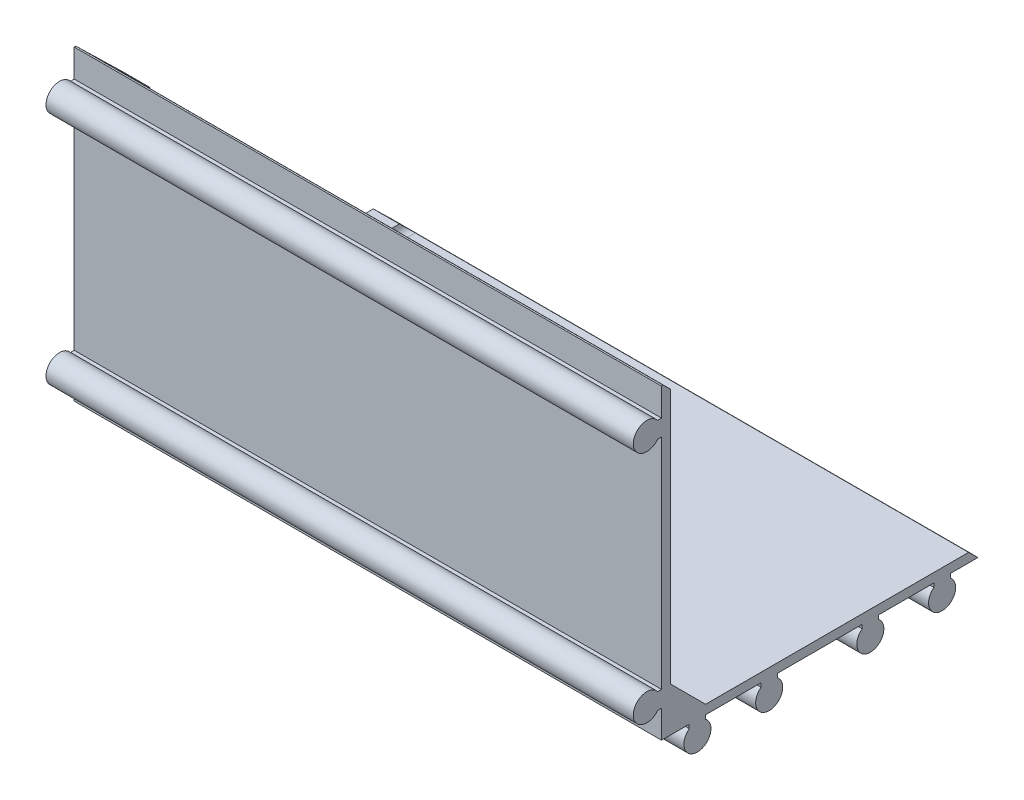
SolidWorks part; units mm, degrees
ref_plane "Спереди" through (0, 0, 0) normal (0, 0, 1) x (1, 0, 0)
ref_plane "Сверху" through (0, 0, 0) normal (0, 1, 0) x (1, 0, 0)
ref_plane "Справа" through (0, 0, 0) normal (1, 0, 0) x (0, 0, -1)
ref_plane "Плоскость4" through (90, 0, 0) normal (1, 0, 0) x (0, 0, -1)
sketch "Эскиз1" plane through (90, 0, 0) normal (1, 0, 0) x (0, 0, -1)
  line L0 (6.75, 160.9062) -> (6.75, 204.25)
  line L1 (6.75, 204.25) -> (-38.0938, 204.25)
  line L2 (-38.0938, 201.75) -> (-37.5, 201.75)
  line L3 (-37.5, 201.75) -> (-37.5, 168.25)
  line L4 (-37.5, 168.25) -> (-38.0938, 168.25)
  line L5 (-38.0938, 165.75) -> (-37.5, 165.75)
  line L6 (-37.5, 165.75) -> (-37.5, 161.5)
  line L7 (-37.5, 161.5) -> (-33.25, 161.5)
  line L8 (-33.25, 161.5) -> (-33.25, 160.9062)
  line L9 (-30.75, 160.9062) -> (-30.75, 161.5)
  line L10 (-30.75, 161.5) -> (-22.25, 161.5)
  line L11 (-22.25, 161.5) -> (-22.25, 160.9062)
  line L12 (-19.75, 160.9062) -> (-19.75, 161.5)
  line L13 (-19.75, 161.5) -> (-6.75, 161.5)
  line L14 (-6.75, 161.5) -> (-6.75, 160.9062)
  line L15 (-4.25, 160.9062) -> (-4.25, 161.5)
  line L16 (-4.25, 161.5) -> (4.25, 161.5)
  line L17 (4.25, 161.5) -> (4.25, 160.9062)
  arc A0 (-38.0938, 204.25) -> (-38.0938, 201.75) centre (-39.75, 203) ccw
  arc A1 (-38.0938, 168.25) -> (-38.0938, 165.75) centre (-39.75, 167) ccw
  arc A2 (-33.25, 160.9062) -> (-30.75, 160.9062) centre (-32, 159.25) ccw
  arc A3 (-22.25, 160.9062) -> (-19.75, 160.9062) centre (-21, 159.25) ccw
  arc A4 (-6.75, 160.9062) -> (-4.25, 160.9062) centre (-5.5, 159.25) ccw
  arc A5 (4.25, 160.9062) -> (6.75, 160.9062) centre (5.5, 159.25) ccw
extrude "Бобышка-Вытянуть1" add sketch "Эскиз1" against normal blind 90
sketch "Эскиз2" plane through (0, 0, -6.75) normal (0, 0, -1) x (-1, 0, 0)
  line L0 (0, 204.25) -> (0, 161.5)
  line L1 (0, 161.5) -> (-90, 161.5)
  line L2 (-90, 161.5) -> (-90, 204.25)
  line L3 (-90, 204.25) -> (0, 204.25)
extrude "Бобышка-Вытянуть2" add sketch "Эскиз2" along normal blind 8.2
sketch "Эскиз3" plane through (0, 204.25, 0) normal (0, 1, 0) x (-1, 0, 0)
  line L0 (-90, -14.95) -> (-90, 37.5)
  line L1 (-90, 37.5) -> (0, 37.5)
  line L2 (0, 37.5) -> (0, -14.95)
  line L3 (0, -14.95) -> (-90, -14.95)
extrude "Бобышка-Вытянуть3" add sketch "Эскиз3" along normal blind 8.2
sketch "Эскиз4" plane through (0, 0, 0) normal (-1, 0, 0) x (0, 0, 1)
  line L0 (-14.95, 161.5) -> (-11, 161.5)
  line L1 (-11, 161.5) -> (-11, 163.75)
  line L2 (-11, 163.75) -> (-14.95, 163.75)
  line L3 (-14.95, 163.75) -> (-14.95, 161.5)
extrude "Вырез-Вытянуть1" cut sketch "Эскиз4" against normal through all
sketch "Эскиз5" plane through (0, 0, 0) normal (-1, 0, 0) x (0, 0, 1)
  line L0 (-14.95, 170.25) -> (-11, 170.25)
  line L1 (-11, 170.25) -> (-11, 199.75)
  line L2 (-11, 199.75) -> (-14.95, 199.75)
  line L3 (-14.95, 199.75) -> (-14.95, 170.25)
extrude "Вырез-Вытянуть2" cut sketch "Эскиз5" against normal through all
sketch "Эскиз6" plane through (0, 0, 0) normal (-1, 0, 0) x (0, 0, 1)
  line L0 (-14.95, 212.45) -> (-14.95, 206.25)
  line L1 (-14.95, 206.25) -> (-11, 206.25)
  line L2 (-11, 206.25) -> (-11, 212.45)
  line L3 (-11, 212.45) -> (-14.95, 212.45)
extrude "Вырез-Вытянуть3" cut sketch "Эскиз6" against normal through all
sketch "Эскиз7" plane through (0, 0, 0) normal (-1, 0, 0) x (0, 0, 1)
  line L0 (-11, 212.45) -> (-11, 208.5)
  line L1 (-11, 208.5) -> (-8.75, 208.5)
  line L2 (-8.75, 208.5) -> (-8.75, 212.45)
  line L3 (-8.75, 212.45) -> (-11, 212.45)
extrude "Вырез-Вытянуть4" cut sketch "Эскиз7" against normal through all
sketch "Эскиз8" plane through (0, 0, 0) normal (-1, 0, 0) x (0, 0, 1)
  line L0 (-2.25, 212.45) -> (-2.25, 208.5)
  line L1 (-2.25, 208.5) -> (2.25, 208.5)
  line L2 (2.25, 208.5) -> (2.25, 212.45)
  line L3 (2.25, 212.45) -> (-2.25, 212.45)
extrude "Вырез-Вытянуть5" cut sketch "Эскиз8" against normal through all
sketch "Эскиз9" plane through (0, 0, 0) normal (-1, 0, 0) x (0, 0, 1)
  line L0 (8.75, 212.45) -> (8.75, 208.5)
  line L1 (8.75, 208.5) -> (17.75, 208.5)
  line L2 (17.75, 208.5) -> (17.75, 212.45)
  line L3 (17.75, 212.45) -> (8.75, 212.45)
extrude "Вырез-Вытянуть6" cut sketch "Эскиз9" against normal through all
sketch "Эскиз10" plane through (0, 0, 0) normal (-1, 0, 0) x (0, 0, 1)
  line L0 (24.25, 212.45) -> (24.25, 208.5)
  line L1 (24.25, 208.5) -> (28.75, 208.5)
  line L2 (28.75, 208.5) -> (28.75, 212.45)
  line L3 (28.75, 212.45) -> (24.25, 212.45)
extrude "Вырез-Вытянуть7" cut sketch "Эскиз10" against normal through all
sketch "Эскиз11" plane through (0, 0, 0) normal (-1, 0, 0) x (0, 0, 1)
  line L0 (37.5, 212.45) -> (35.25, 212.45)
  line L1 (35.25, 212.45) -> (35.25, 208.5)
  line L2 (35.25, 208.5) -> (37.5, 208.5)
  line L3 (37.5, 208.5) -> (37.5, 212.45)
extrude "Вырез-Вытянуть8" cut sketch "Эскиз11" against normal through all
sketch "Эскиз12" plane through (90, 0, 0) normal (1, 0, 0) x (0, 0, -1)
  line L0 (9.6, 207.1) -> (-36.1, 207.1)
  line L1 (-36.1, 207.1) -> (-36.1, 162.9)
  line L2 (-36.1, 162.9) -> (9.6, 162.9)
  line L3 (9.6, 162.9) -> (9.6, 207.1)
extrude "Вырез-Вытянуть9" cut sketch "Эскиз12" against normal blind 86
hole_wizard "Диаметр отверстия Ø2.5 (2.5)1" positions "Эскиз14" profile "Эскиз13" hole size "Ø2.5" standard "Ansi Metric"
sketch "Эскиз14" plane through (90, 0, 0) normal (1, 0, 0) x (0, 0, -1)
  point P0 (5.5, 159.25)
  point P1 (-21, 159.25)
  point P2 (-5.5, 159.25)
  point P3 (-32, 159.25)
  point P4 (-39.75, 167)
  point P5 (-39.75, 203)
sketch "Эскиз13" plane through (90, 159.25, -5.5) normal (0, 1, 0) x (0, 0, -1)
  line L0 (0, 0) -> (0, 90)
  line L1 (0, 90) -> (1.25, 90)
  line L2 (1.25, 90) -> (1.25, 0)
  line L5 (1.25, 0) -> (0, 0)
  line L11 (0, -6.35) -> (0, 107.95) construction
  dimension "Диаметр сквозного отверстия" = 2.5
  dimension "Глубина сквозного отверстия" = 90
hole_wizard "Диаметр отверстия Ø4.5 (4.5)1" positions "Эскиз16" profile "Эскиз15" hole size "Ø4.5" standard "Ansi Metric"
sketch "Эскиз16" plane through (0, 0, 0) normal (-1, 0, 0) x (0, 0, 1)
  point P0 (-13.25, 167)
  point P1 (-13.25, 203)
  point P2 (-5.5, 210.75)
  point P3 (5.5, 210.75)
  point P4 (21, 210.75)
  point P5 (32, 210.75)
sketch "Эскиз15" plane through (0, 167, -13.25) normal (0, 1, 0) x (0, 0, 1)
  line L0 (0, 0) -> (0, 90)
  line L1 (0, 90) -> (2.25, 90)
  line L2 (2.25, 90) -> (2.25, 0)
  line L5 (2.25, 0) -> (0, 0)
  line L11 (0, -6.35) -> (0, 107.95) construction
  dimension "Диаметр сквозного отверстия" = 4.5
  dimension "Глубина сквозного отверстия" = 90
hole_wizard "Диаметр отверстия Ø8.3 (8.3)1" positions "Эскиз18" profile "Эскиз17" hole size "Ø8.3" standard "Ansi Metric"
sketch "Эскиз18" plane through (0, 0, 0) normal (-1, 0, 0) x (0, 0, 1)
  point P0 (13.25, 185)
sketch "Эскиз17" plane through (0, 185, 13.25) normal (0, 1, 0) x (0, 0, 1)
  line L0 (0, 0) -> (0, 3.2)
  line L1 (0, 3.2) -> (4.15, 3.2)
  line L2 (4.15, 3.2) -> (4.15, 0)
  line L5 (4.15, 0) -> (0, 0)
  line L10 (0, 3.2) -> (-4.15, 3.2) construction
  line L11 (0, -6.35) -> (0, 107.95) construction
  dimension "Диаметр отверстия" = 8.3
  dimension "Глубина отверстия" = 3.2
  dimension "Угол заточки сверла" = 180
sketch "Эскиз19" plane through (90, 0, 0) normal (1, 0, 0) x (0, 0, -1)
  circle A0 centre (-39.75, 203) radius 1.6725
  circle A1 centre (-39.75, 167) radius 1.4592
  circle A2 centre (-32, 159.25) radius 1.4599
  circle A3 centre (-21, 159.25) radius 1.5928
  circle A4 centre (-5.5, 159.25) radius 1.5322
  circle A5 centre (5.5, 159.25) radius 1.5961
extrude "Бобышка-Вытянуть4" add sketch "Эскиз19" against normal blind 90
sketch "Эскиз20" plane through (0, 0, 0) normal (-1, 0, 0) x (0, 0, 1)
  circle A0 centre (13.25, 185) radius 4.15
extrude "Вырез-Вытянуть10" cut sketch "Эскиз20" against normal blind 90
fillet "Скругление1" radius 2 1 edges at (45, 208.5, -8.75)
fillet "Скругление2" radius 2 1 edges at (45, 163.75, -11)
fillet "Скругление3" radius 2 1 edges at (45, 170.25, -11)
fillet "Скругление4" radius 2 1 edges at (45, 199.75, -11)
fillet "Скругление5" radius 2 1 edges at (45, 206.25, -11)
fillet "Скругление6" radius 2 1 edges at (45, 208.5, -2.25)
fillet "Скругление7" radius 2 1 edges at (45, 208.5, 2.25)
fillet "Скругление8" radius 2 1 edges at (45, 208.5, 8.75)
fillet "Скругление9" radius 2 1 edges at (45, 208.5, 17.75)
fillet "Скругление10" radius 2 1 edges at (45, 208.5, 24.25)
fillet "Скругление11" radius 2 1 edges at (45, 208.5, 28.75)
fillet "Скругление12" radius 2 1 edges at (45, 208.5, 35.25)
fillet "Скругление13" radius 1.2 4 edges at (4, 185, -9.6) (4, 162.9, 13.25) (4, 185, 36.1) (4, 207.1, 13.25)
sketch "Эскиз21" plane through (90, 0, 0) normal (1, 0, 0) x (0, 0, -1)
  line L0 (-37.25, 208.5) -> (11, 161.5)
  line L1 (11, 161.5) -> (17.9034, 161.5)
  line L2 (17.9034, 161.5) -> (17.9034, 214.8833)
  line L3 (17.9034, 214.8833) -> (-37.25, 214.8833)
  line L4 (-37.25, 214.8833) -> (-37.25, 208.5)
extrude "Вырез-Вытянуть11" cut sketch "Эскиз21" against normal blind 131
sketch "Эскиз22" plane through (0, 0, 0) normal (-1, 0, 0) x (0, 0, 1)
  line L0 (16.1612, 187.9576) -> (10.217, 182.1674)
  arc A0 (10.217, 182.1674) -> (16.1612, 187.9576) centre (13.25, 185) ccw construction
  arc A1 (10.217, 182.1674) -> (16.1612, 187.9576) centre (13.25, 185) ccw
extrude "Бобышка-Вытянуть5" add sketch "Эскиз22" against normal blind 4
sketch "Эскиз23" plane through (4, 0, 0) normal (1, 0, 0) x (0, 0, -1)
  line L2 (-29.9, 205.9) -> (8.3309, 169.1)
  line L4 (-29.9, 169.1) -> (8.3309, 169.1)
  line L5 (-29.9, 205.9) -> (-29.9, 169.1)
  line L6 (-29.9, 169.1) -> (8.3309, 169.1)
  line L7 (-29.9, 205.9) -> (-29.9, 169.1)
  dimension "D1" = 5
extrude "Вырез-Вытянуть12" cut sketch "Эскиз23" against normal blind 4
sketch "Эскиз25" plane through (4, 0, 0) normal (1, 0, 0) x (0, 0, -1)
  line L0 (-34.9, 164.1) -> (8.3309, 164.1) construction
  line L1 (-29.9, 164.1) -> (8.3309, 164.1)
  line L2 (-29.9, 169.1) -> (-29.9, 164.1)
  line L3 (-29.9, 169.1) -> (3.1979, 169.1) construction
  line L4 (3.1979, 169.1) -> (8.3309, 164.1) construction
  line L5 (-29.9, 169.1) -> (3.1979, 169.1)
  line L6 (3.1979, 169.1) -> (8.3309, 164.1)
extrude "Вырез-Вытянуть14" cut sketch "Эскиз25" against normal blind 6
sketch "Эскиз26" plane through (4, 0, 0) normal (1, 0, 0) x (0, 0, -1)
  line L0 (-29.9, 201.3404) -> (-29.9, 164.1) construction
  line L1 (-29.9, 164.1) -> (8.3309, 164.1) construction
  line L2 (-29.9, 184.1) -> (-19.75, 164.1)
  line L3 (-29.9, 184.1) -> (-29.9, 164.1)
  line L4 (-29.9, 164.1) -> (-19.75, 164.1)
  point P0 (-29.9, 184.1)
  point P1 (-19.75, 164.1)
  dimension "D1" = 20
extrude "Бобышка-Вытянуть6" add sketch "Эскиз26" against normal blind 4
sketch "Эскиз27" plane through (90, 0, 0) normal (1, 0, 0) x (0, 0, -1)
  line L0 (-36.1, 162.9) -> (-36.1, 207.1) construction
  line L1 (-36.1, 162.9) -> (9.5628, 162.9) construction
  line L2 (9.5628, 162.9) -> (-36.1, 162.9) construction
  line L3 (-30.75, 162.9) -> (-36.1, 162.9)
  line L4 (-36.1, 162.9) -> (-36.1, 168.25)
  line L5 (-36.1, 168.25) -> (-30.75, 162.9)
  point P0 (-36.1, 168.25)
  point P1 (-30.75, 162.9)
extrude "Бобышка-Вытянуть7" add sketch "Эскиз27" against normal blind 87
sketch "Эскиз28" plane through (90, 0, 0) normal (1, 0, 0) x (0, 0, -1)
  line L0 (-36.1, 207.1) -> (-35.8128, 207.1) construction
  line L1 (-36.1, 207.1) -> (-35.8128, 207.1)
  line L2 (-37.25, 208.5) -> (-35.8128, 207.1) construction
  line L3 (-36.1, 207.3798) -> (-35.8128, 207.1)
  line L4 (-36.1, 207.1) -> (-36.1, 207.3798)
extrude "Вырез-Вытянуть15" cut sketch "Эскиз28" against normal blind 84.5
